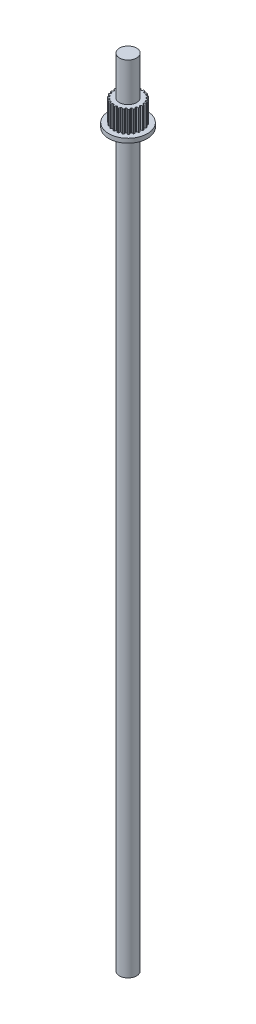
SolidWorks part; units mm, degrees
ref_plane "Front Plane" through (0, 0, 0) normal (0, 0, 1) x (1, 0, 0)
ref_plane "Top Plane" through (0, 0, 0) normal (0, 1, 0) x (1, 0, 0)
ref_plane "Right Plane" through (0, 0, 0) normal (1, 0, 0) x (0, 0, -1)
sketch "Sketch1" plane through (0, 0, 0) normal (0, 1, 0) x (1, 0, 0)
  circle A0 centre (0, 0) radius 4
  circle A1 centre (0, 0) radius 6
  dimension "D1" = 8
  dimension "D2" = 12
extrude "Boss-Extrude1" add sketch "Sketch1" along normal blind 10
sketch "Sketch2" plane through (0, 0, 0) normal (0, -1, 0) x (1, 0, 0)
  line L0 (0, 0) -> (0, 6.9454) construction
  line L1 (-0.35, 6.74) -> (0.35, 6.74)
  line L2 (-0.605, 5.9694) -> (-0.605, 5.6922)
  line L3 (-0.605, 5.6922) -> (0.6374, 5.6922)
  line L4 (0.6374, 5.6922) -> (0.605, 5.9694)
  circle A0 centre (0, 0) radius 6 construction
  spline S0 degree 2 poles (-0.605, 5.9694) (-0.2987, 6.2952) (-0.35, 6.74) knots 0 0 0 1 1 1
  spline S1 degree 2 poles (0.605, 5.9694) (0.2987, 6.2952) (0.35, 6.74) knots 0 0 0 1 1 1
  dimension "D1" = 6.74
  dimension "D2" = 0.7
  dimension "D3" = 1.21
extrude "Boss-Extrude2" add sketch "Sketch2" against normal up to surface (10 mm away) up to face at (0, 10, 6)
fillet "Fillet1" radius 0.1 2 edges at (-0.35, 5, 6.74) (0.35, 5, 6.74)
pattern_circular "CirPattern2" count 23 over 360 of "Fillet1", "Boss-Extrude2"
sketch "Sketch4" plane through (0, 0, 0) normal (0, -1, 0) x (1, 0, 0)
  circle A0 centre (0, 0) radius 4 construction
  circle A1 centre (0, 0) radius 4
  circle A2 centre (0, 0) radius 9
  dimension "D1" = 5
extrude "Boss-Extrude4" add sketch "Sketch4" along normal blind 2
sketch "Sketch7" plane through (0, 10, 0) normal (0, 1, 0) x (1, 0, 0)
  circle A1 centre (0, 0) radius 4 construction
  circle A2 centre (0, 0) radius 7.2
  circle A3 centre (0, 0) radius 7.2
  circle A4 centre (0, 0) radius 4
  dimension "D1" = 3.2
extrude "Boss-Extrude7" [suppressed] add sketch "Sketch7" along normal blind 2
fillet "Fillet3" [suppressed] radius 1.5
sketch "Sketch5" plane through (0, 10, 0) normal (0, 1, 0) x (1, 0, 0)
  circle A1 centre (0, 0) radius 4 construction
  circle A2 centre (0, 0) radius 2.49
  circle A3 centre (0, 0) radius 2.49
  circle A4 centre (0, 0) radius 4
  dimension "D1" = 1.51
extrude "Boss-Extrude5" [suppressed] add sketch "Sketch5" against normal up to surface (12 mm away) contours A4 A3
sketch "Sketch6" [suppressed] plane through (0, 10, 0) normal (0, 1, 0) x (1, 0, 0)
  circle A0 centre (0, 0) radius 2.49 construction
  circle A1 centre (0, 0) radius 2.49
  circle A2 centre (0, 0) radius 6.99
  dimension "D1" = 4.5
extrude "Boss-Extrude6" [suppressed] add sketch "Sketch6" along normal blind 2
fillet "Fillet2" [suppressed] radius 1.5
sketch "Sketch3" plane through (0, -2, 0) normal (0, -1, 0) x (1, 0, 0)
  circle A1 centre (0, 0) radius 4
  point P1 (0, 0)
extrude "Boss-Extrude3" add sketch "Sketch3" along normal blind 340 and the other way blind 30
